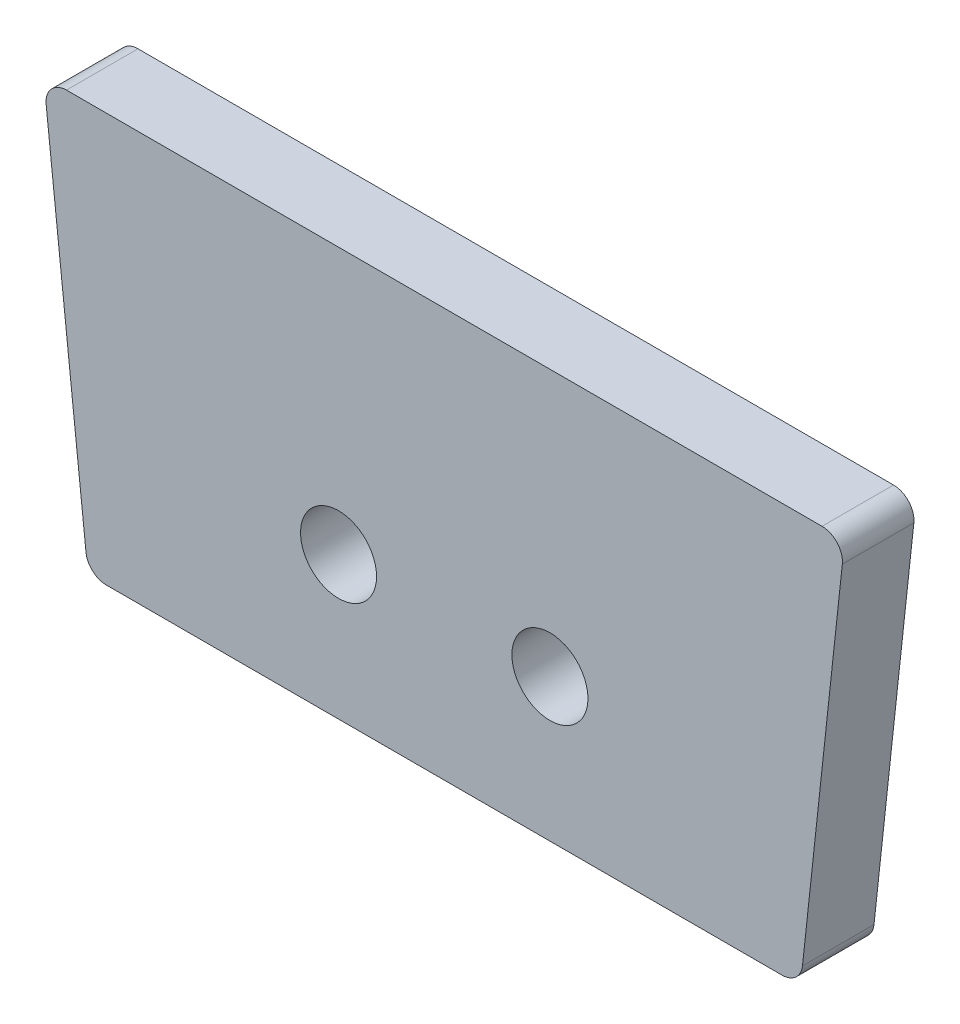
SolidWorks part; units mm, degrees
ref_plane "前视基准面" through (0, 0, 0) normal (0, 0, 1) x (1, 0, 0)
ref_plane "上视基准面" through (0, 0, 0) normal (0, 1, 0) x (1, 0, 0)
ref_plane "右视基准面" through (0, 0, 0) normal (1, 0, 0) x (0, 0, -1)
sketch "草图1" plane through (0, 0, 0) normal (0, 0, 1) x (1, 0, 0)
  line L0 (-17.4335, -14.3326) -> (-19.6001, 5.6674)
  line L1 (-20.4553, 18.2099) -> (20.4553, 18.2099) construction
  line L2 (-20.4553, 18.2099) -> (-20.4553, -7.3592) construction
  line L3 (-20.4553, -7.3592) -> (20.4553, -7.3592) construction
  line L4 (20.4553, 18.2099) -> (20.4553, -7.3592) construction
  line L5 (-17.4335, -14.3326) -> (17.4335, -14.3326)
  line L6 (0, 18.2099) -> (0, -18.2099) construction
  line L9 (17.4335, -14.3326) -> (19.6001, 5.6674)
  line L11 (-19.6001, 5.6674) -> (19.6001, 5.6674)
  circle A0 centre (-5.1719, -7.3592) radius 1.8596
  circle A1 centre (5.1719, -7.3592) radius 1.8596
  point P12 (0, -14.3326)
  dimension "D1" = 20
extrude "凸台-拉伸1" add sketch "草图1" along normal blind 3.5
fillet "圆角1" radius 1 4 edges at (19.6001, 5.6674, 1.75) (17.4335, -14.3326, 1.75) (-17.4335, -14.3326, 1.75) (-19.6001, 5.6674, 1.75)
